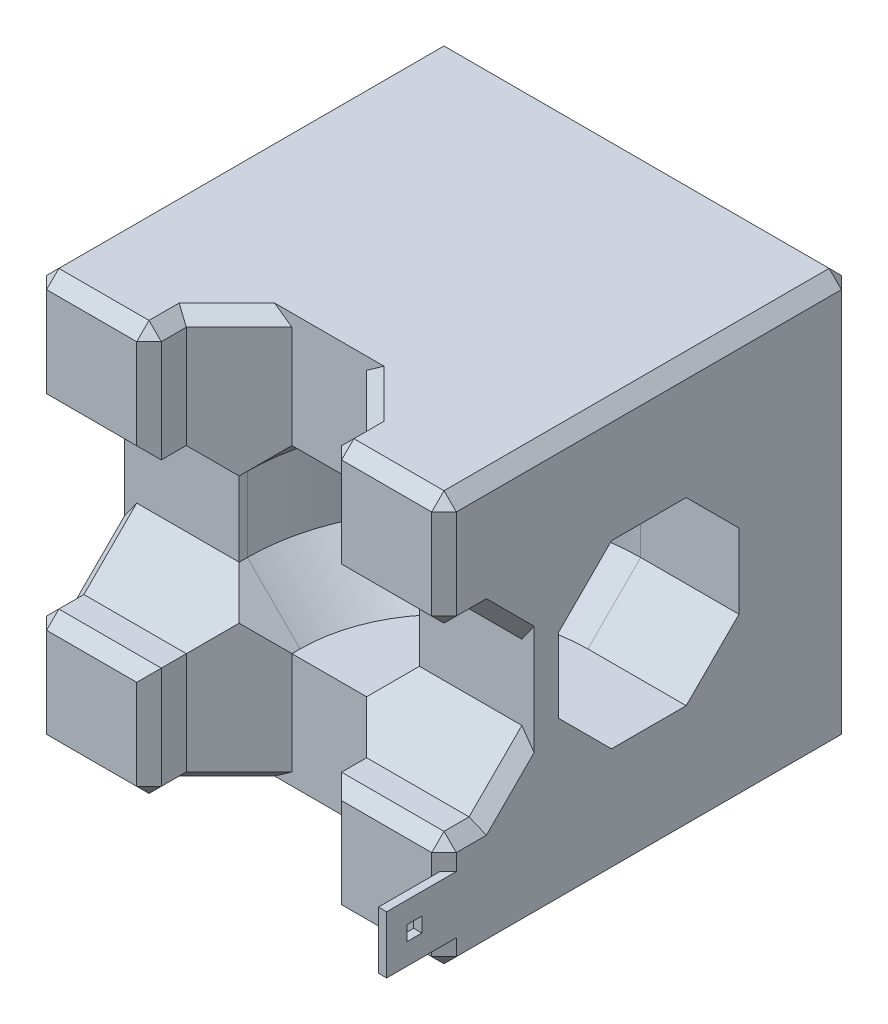
SolidWorks part; units mm, degrees
ref_plane "Front" through (0, 0, 0) normal (0, 0, 1) x (1, 0, 0)
ref_plane "Top" through (0, 0, 0) normal (0, 1, 0) x (1, 0, 0)
ref_plane "Right" through (0, 0, 0) normal (1, 0, 0) x (0, 0, -1)
sketch "Sketch1" plane through (0, 0, 0) normal (0, 0, 1) x (1, 0, 0)
  line L1 (0, 0) -> (50, 0)
  line L2 (0, 0) -> (0, 50)
  line L3 (0, 50) -> (50, 50)
  line L4 (50, 0) -> (50, 50)
  dimension "D1" = 50
extrude "Boss-Extrude1" add sketch "Sketch1" along normal blind 50
sketch "Sketch2" plane through (0, 0, 0) normal (0, 1, 0) x (0, 0, 1)
  line L0 (50, 0) -> (50, 50) construction
  line L10 (39, 36) -> (61, 36) construction
  line L11 (39, 36) -> (39, 14) construction
  line L12 (39, 14) -> (61, 14) construction
  line L13 (61, 36) -> (61, 14) construction
  line L14 (61, 29.5563) -> (54.5563, 36)
  line L15 (39, 36) -> (61, 14) construction
  line L16 (54.5563, 36) -> (45.4437, 36)
  line L17 (39, 14) -> (61, 36) construction
  line L26 (45.4437, 36) -> (39, 29.5563)
  line L27 (39, 29.5563) -> (39, 20.4437)
  line L28 (39, 20.4437) -> (45.4437, 14)
  line L29 (45.4437, 14) -> (54.5563, 14)
  line L30 (54.5563, 14) -> (61, 20.4437)
  line L31 (61, 20.4437) -> (61, 29.5563)
  circle A1 centre (50, 25) radius 11 construction
  point P5 (50, 25)
  dimension "D1" = 22
sketch "Sketch6" plane through (0, 0, 0) normal (1, 0, 0) x (0, 0, -1)
  line L0 (-50, 25) -> (0, 25) construction
  line L1 (-61, 29.5563) -> (-61, 20.4437)
  line L2 (-61, 20.4437) -> (-54.5563, 14)
  line L3 (-54.5563, 14) -> (-45.4437, 14)
  line L4 (-45.4437, 14) -> (-39, 20.4437)
  line L5 (-39, 20.4437) -> (-39, 29.5563)
  line L6 (-39, 29.5563) -> (-45.4437, 36)
  line L7 (-45.4437, 36) -> (-54.5563, 36)
  line L8 (-54.5563, 36) -> (-61, 29.5563)
  line L9 (0, 0) -> (0, 50) construction
  line L10 (-50, 50) -> (-50, 0) construction
  circle A0 centre (-50, 25) radius 11 construction
  dimension "D1" = 22
extrude "Cut-Extrude3" cut sketch "Sketch2" along normal through all
extrude "Cut-Extrude4" cut sketch "Sketch6" along normal through all
ref_plane "Plane1" through (0, 25, 0) normal (0, -1, 0) x (-1, 0, 0)
sketch "Sketch8" plane through (50, 0, 0) normal (1, 0, 0) x (0, 0, -1)
  line L0 (-25, 0) -> (-25, 25) construction
  line L1 (-14, 14) -> (-36, 14) construction
  line L2 (-14, 14) -> (-14, 36) construction
  line L3 (-14, 36) -> (-36, 36) construction
  line L4 (-36, 14) -> (-36, 36) construction
  line L5 (-14, 14) -> (-36, 36) construction
  line L6 (-14, 36) -> (-36, 14) construction
  line L7 (-25, 25) -> (0, 25) construction
  line L8 (-50, 0) -> (0, 0) construction
  line L9 (0, 0) -> (0, 50) construction
  line L11 (-14, 29.5563) -> (-20.4437, 36)
  line L12 (-20.4437, 36) -> (-29.5563, 36)
  line L13 (-29.5563, 36) -> (-36, 29.5563)
  line L14 (-36, 29.5563) -> (-36, 20.4437)
  line L15 (-36, 20.4437) -> (-29.5563, 14)
  line L16 (-29.5563, 14) -> (-20.4437, 14)
  line L17 (-20.4437, 14) -> (-14, 20.4437)
  line L18 (-14, 20.4437) -> (-14, 29.5563)
  circle A0 centre (-25, 25) radius 11 construction
  point P0 (-25, 25)
  dimension "D1" = 22
sketch "Sketch9" plane through (0, 25, 0) normal (0, -1, 0) x (-1, 0, 0)
  line L0 (-50, -25) -> (-38, -25)
  line L1 (-25, -50) -> (-25, -38)
  line L2 (-36, -50) -> (-14, -50) construction
  line L3 (-29.5563, -39) -> (-20.4437, -39) construction
  arc A0 (-38, -25) -> (-25, -38) centre (-38, -38) cw
  dimension "D1" = 1
sweep "Cut-Sweep5" cut profiles "Sketch8" path "Sketch9"
chamfer "Chamfer1" distance 1.5 angle 45 40 edges at (0, 17.2218, 42.2218) (0, 14, 47.7218) (25, 50, 0) (14, 43, 50) (17.2218, 50, 42.2218) (14, 50, 47.7218) (7, 50, 50) (0, 32.7782, 42.2218) (0, 36, 47.7218) (7, 36, 50) (0, 43, 50) (0, 50, 25) (0, 25, 0) (32.7782, 50, 42.2218) (36, 50, 47.7218) (0, 7, 50) (7, 14, 50) (14, 7, 50) (17.2218, 0, 42.2218) (14, 0, 47.7218) (7, 0, 50) (0, 0, 25) (25, 0, 0) (50, 32.7782, 42.2218) (50, 36, 47.7218) (43, 50, 50) (36, 43, 50) (43, 36, 50) (50, 43, 50) (50, 50, 25) (50, 25, 0) (50, 0, 25) (43, 14, 50) (36, 7, 50) (50, 17.2218, 42.2218) (50, 14, 47.7218) (50, 7, 50) (43, 0, 50) (32.7782, 0, 42.2218) (36, 0, 47.7218)
sketch "Sketch10" plane through (0, 0, 50) normal (0, 0, 1) x (1, 0, 0)
  line L0 (50, 12.5) -> (50, 1.5) construction
  line L1 (50, 10.5) -> (49, 10.5)
  line L2 (50, 10.5) -> (50, 3.5)
  line L3 (50, 3.5) -> (49, 3.5)
  line L4 (49, 10.5) -> (49, 3.5)
  point P6 (50, 7)
  dimension "D1" = 7
  dimension "D2" = 1
extrude "Boss-Extrude2" add sketch "Sketch10" along normal blind 7 and the other way blind 10
sketch "Sketch11" plane through (50, 0, 0) normal (1, 0, 0) x (0, 0, -1)
  line L0 (-54.5, 7) -> (-57, 7) construction
  line L1 (-54.5, 6.1) -> (-52.7, 6.1)
  line L2 (-54.5, 6.1) -> (-54.5, 7.9)
  line L3 (-54.5, 7.9) -> (-52.7, 7.9)
  line L4 (-52.7, 6.1) -> (-52.7, 7.9)
  line L5 (-57, 3.5) -> (-57, 10.5) construction
  dimension "D1" = 2.5
  dimension "D2" = 1.8
extrude "Cut-Extrude5" cut sketch "Sketch11" against normal blind 7
